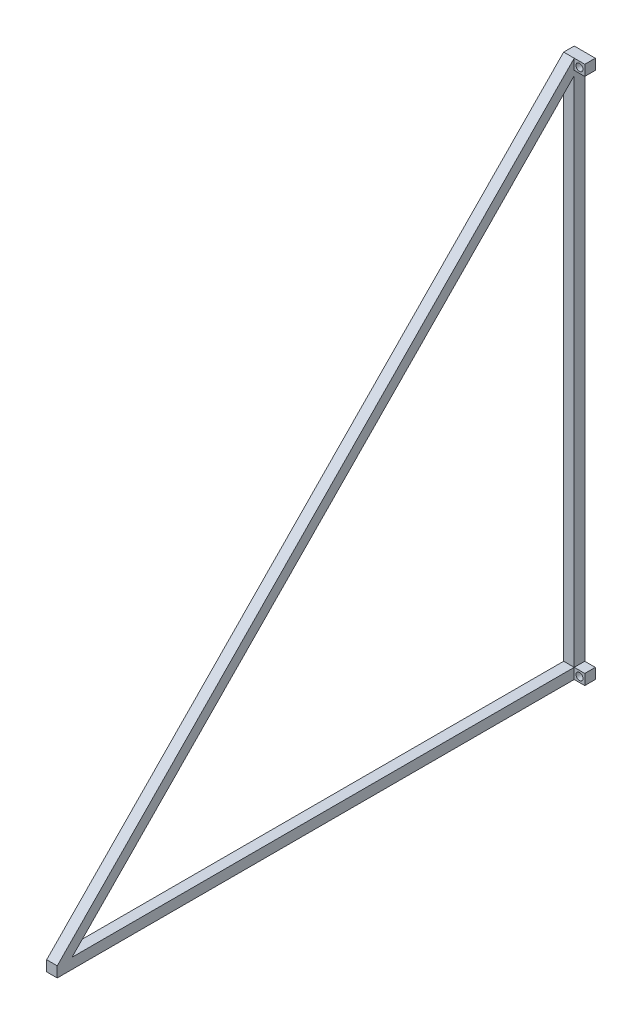
SolidWorks part; units mm, degrees
ref_plane "Přední rovina" through (0, 0, 0) normal (0, 0, 1) x (1, 0, 0)
ref_plane "Horní rovina" through (0, 0, 0) normal (0, 1, 0) x (1, 0, 0)
ref_plane "Pravá rovina" through (0, 0, 0) normal (1, 0, 0) x (0, 0, -1)
sketch "Skica1" plane through (0, 0, 0) normal (0, 0, 1) x (1, 0, 0)
  line L0 (3, 150) -> (3, 153)
  line L1 (0, 0) -> (3, 0)
  line L2 (0, 0) -> (0, 3)
  line L3 (0, 3) -> (3, 3)
  line L4 (3, 0) -> (3, 3)
  line L5 (3, 0) -> (6, 0)
  line L6 (3, 0) -> (3, 3)
  line L7 (3, 3) -> (6, 3)
  line L8 (6, 0) -> (6, 3)
  line L9 (0, 3) -> (3, 3)
  line L10 (0, 3) -> (0, 153)
  line L11 (0, 153) -> (3, 153)
  line L12 (3, 3) -> (3, 153)
  line L13 (0, 153) -> (3, 153)
  line L14 (0, 153) -> (0, 150)
  line L15 (0, 150) -> (3, 150)
  line L16 (3, 153) -> (3, 150)
  line L17 (3, 150) -> (6, 150)
  line L18 (6, 150) -> (6, 153)
  line L19 (3, 153) -> (6, 153)
  line L20 (-3.3264, 0.8843) -> (-3.3264, 3.8843)
  line L21 (-6.3264, 3.8843) -> (-3.3264, 3.8843)
  line L22 (-6.3264, 0.8843) -> (-6.3264, 3.8843)
  line L23 (-6.3264, 0.8843) -> (-3.3264, 0.8843)
  circle A0 centre (4.5, 1.5) radius 1
  circle A1 centre (4.5, 151.5) radius 1
  circle A2 centre (-4.8264, 2.3843) radius 1
  dimension "D4" = 2
  dimension "D5" = 1.5
  dimension "D6" = 1.5
  dimension "D10" = 150
  dimension "D1" = 3
  dimension "D2" = 3
  dimension "D3" = 3
  dimension "D7" = 3
  dimension "D8" = 150
  dimension "D9" = 2
extrude "Přidat vysunutím1" add sketch "Skica1" along normal blind 3 contours L19 L0 L17 L18 A1 | L10 L15 L0 L11 | L15 L10 L3 L12 | L1 L4 L3 L2 | L5 L8 L7 L4 A0
sketch "Skica6" plane through (0, 0, 0) normal (-1, 0, 0) x (0, 0, 1)
  line L0 (3, 153) -> (150, 3)
  line L1 (0, 0) -> (3, 0)
  line L2 (0, 0) -> (0, 153)
  line L3 (0, 153) -> (3, 153)
  line L4 (3, 0) -> (3, 153)
  line L5 (0, 0) -> (150, 0)
  line L6 (0, 0) -> (0, 3)
  line L7 (0, 3) -> (150, 3)
  line L8 (150, 0) -> (150, 3)
  line L9 (3, 148.7138) -> (145.7996, 3)
  line L10 (0.8574, 150.9002) -> (147.8574, 0.9002) construction
  dimension "D1" = 150
  dimension "D3" = 3
  dimension "D2" = 3
extrude "Přidat vysunutím3" add sketch "Skica6" against normal blind 3
